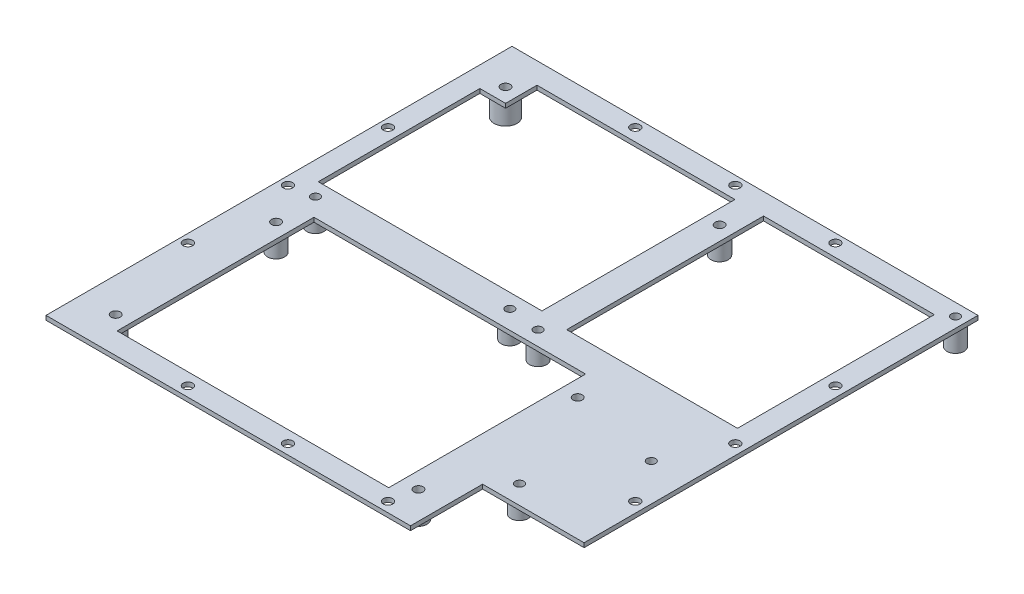
SolidWorks part; units mm, degrees
ref_plane "Alzado" through (0, 0, 0) normal (0, 0, 1) x (1, 0, 0)
ref_plane "Planta" through (0, 0, 0) normal (0, 1, 0) x (1, 0, 0)
ref_plane "Vista lateral" through (0, 0, 0) normal (1, 0, 0) x (0, 0, -1)
sketch "Croquis1" plane through (0, 0, 0) normal (0, 1, 0) x (1, 0, 0)
  line L5 (-74, -74) -> (-74, -8) construction
  line L6 (-74, -74) -> (74, -74) construction
  line L7 (-81.1531, -81.7231) -> (81.8469, -81.7231)
  line L8 (-81.1531, -81.7231) -> (-81.1531, 81.2769)
  line L9 (-81.1531, 81.2769) -> (81.8469, 81.2769)
  line L10 (81.8469, -81.7231) -> (81.8469, 81.2769)
  line L12 (-74, 73.859) -> (74, 73.859) construction
  line L17 (74, -74) -> (74, 73.859) construction
  line L18 (31, -5.141) -> (31, -74)
  line L19 (31, -74) -> (-64, -74)
  line L20 (-64, -74) -> (-64, -5.141)
  line L21 (-64, -5.141) -> (31, -5.141)
  line L22 (-74, 73.859) -> (-74, -5.141) construction
  line L23 (-74, -5.141) -> (3, -5.141) construction
  line L25 (71.346, -16.0316) -> (68.846, -16.0316) construction
  line L26 (46.346, -56.5) -> (71.346, -56.5) construction
  line L27 (-74, -8) -> (41.5, -8) construction
  line L28 (41.5, -8) -> (41.5, -78.25) construction
  line L29 (46.346, -56.5) -> (46.346, -13.5) construction
  line L30 (46.346, -13.5) -> (71.346, -13.5) construction
  line L31 (71.346, -56.5) -> (71.346, -13.5) construction
  line L32 (46.346, -56.5) -> (71.346, -13.5) construction
  line L33 (46.346, -13.5) -> (71.346, -56.5) construction
  line L34 (68.846, -13.5) -> (68.846, -20) construction
  line L35 (46.346, -48.6474) -> (52.646, -48.6474) construction
  line L36 (52.646, -56.5) -> (52.646, -49.9) construction
  line L41 (78.25, 0) -> (78.25, 76.9993) construction
  line L47 (74, 73.859) -> (14.25, 73.859)
  line L48 (74, 73.859) -> (74, 5)
  line L49 (74, 5) -> (14.25, 5)
  line L50 (14.25, 73.859) -> (14.25, 5)
  line L53 (-70, 67.859) -> (-70, 62.876) construction
  line L54 (-65, 62.876) -> (-65, 73.859)
  line L55 (-65, 62.876) -> (-74, 62.876)
  line L57 (-65, 73.859) -> (4.25, 73.859)
  line L59 (-65, 6.3593) -> (4.25, 6.3593)
  line L60 (4.25, 73.859) -> (4.25, 6.3593)
  line L61 (-65, 6.3593) -> (-74, 6.3593)
  line L62 (-74, 62.876) -> (-74, 6.3593)
  line L64 (81.8469, -81.7231) -> (46.346, -81.7231)
  line L65 (81.8469, -81.7231) -> (81.8469, -56.5)
  line L66 (81.8469, -56.5) -> (46.346, -56.5)
  line L67 (46.346, -81.7231) -> (46.346, -56.5)
  circle A0 centre (-78.25, 0) radius 1.65
  circle A1 centre (-78.25, -35) radius 1.65
  circle A2 centre (-35, -78.25) radius 1.65
  circle A3 centre (0, -78.25) radius 1.65
  circle A4 centre (35, -78.25) radius 1.65
  circle A5 centre (78.25, -35) radius 1.65
  circle A6 centre (78.25, 0) radius 1.65
  circle A7 centre (78.25, 35) radius 1.65
  circle A8 centre (35, 78.25) radius 1.65
  circle A9 centre (0, 78.25) radius 1.65
  circle A10 centre (-35, 78.25) radius 1.65
  circle A11 centre (-78.25, 35) radius 1.65
  circle A12 centre (-69.2, -69.3) radius 1.6
  circle A13 centre (-69.2, -13.2) radius 1.6
  circle A14 centre (36.7, -13.6) radius 1.6
  circle A15 centre (36.7, -69.3) radius 1.6
  circle A16 centre (52.646, -49.9) radius 1.5
  circle A17 centre (68.846, -20) radius 1.5
  circle A18 centre (-70, 67.859) radius 1.5
  circle A19 centre (-70, 1.3593) radius 1.5
  circle A20 centre (-2, 1.3593) radius 1.5
  circle A21 centre (78.25, 76.9993) radius 1.5
  circle A22 centre (9.25, 63.5) radius 1.5
  circle A23 centre (9.25, 0) radius 1.5
  point P0 (0, 0)
  point P6 (0, 0)
  point P11 (0, 0)
  point P40 (0, 0)
  point P59 (58.846, -35)
extrude "Saliente-Extruir2" add sketch "Croquis1" along normal blind 1.5 contours L7 L67 L66 L10 L9 L8 A23 A22 A21 A20 A19 A18 A17 A16 A15 A14 A13 A12 A11 A10 A9 A8 A7 A6 A5 A4 A3 A2
sketch "Croquis4" plane through (0, 0, 0) normal (0, -1, 0) x (1, 0, 0)
  circle A0 centre (-69.2, 69.3) radius 3
  circle A1 centre (-69.2, 13.2) radius 3
  circle A2 centre (36.7, 13.6) radius 3
  circle A3 centre (52.646, 49.9) radius 3
  circle A4 centre (68.846, 20) radius 3
  circle A5 centre (9.25, 0) radius 3
  circle A6 centre (-2, -1.3593) radius 3
  circle A7 centre (-70, -1.3593) radius 3
  circle A8 centre (-70, -67.859) radius 4
  circle A9 centre (9.25, -63.5) radius 3
  circle A10 centre (78.25, -76.9993) radius 3
  circle A11 centre (36.7, 69.3) radius 3
extrude "Saliente-Extruir3" add sketch "Croquis4" along normal blind 7.6
sketch "Croquis5" plane through (0, 1.5, 0) normal (0, 1, 0) x (1, 0, 0)
  circle A0 centre (-69.2, -13.2) radius 1.6
  circle A1 centre (-70, 1.3593) radius 1.5
  circle A2 centre (-2, 1.3593) radius 1.5
  circle A3 centre (9.25, 0) radius 1.5
  circle A4 centre (36.7, -13.6) radius 1.6
  circle A5 centre (36.7, -69.3) radius 1.6
  circle A6 centre (52.646, -49.9) radius 1.5
  circle A7 centre (68.846, -20) radius 1.5
  circle A8 centre (9.25, 63.5) radius 1.6
  circle A9 centre (-70, 67.859) radius 1.6
  circle A10 centre (-69.2, -69.3) radius 1.6
  circle A11 centre (78.25, 76.9993) radius 1.5
extrude "Cortar-Extruir2" cut sketch "Croquis5" against normal blind 17.6
